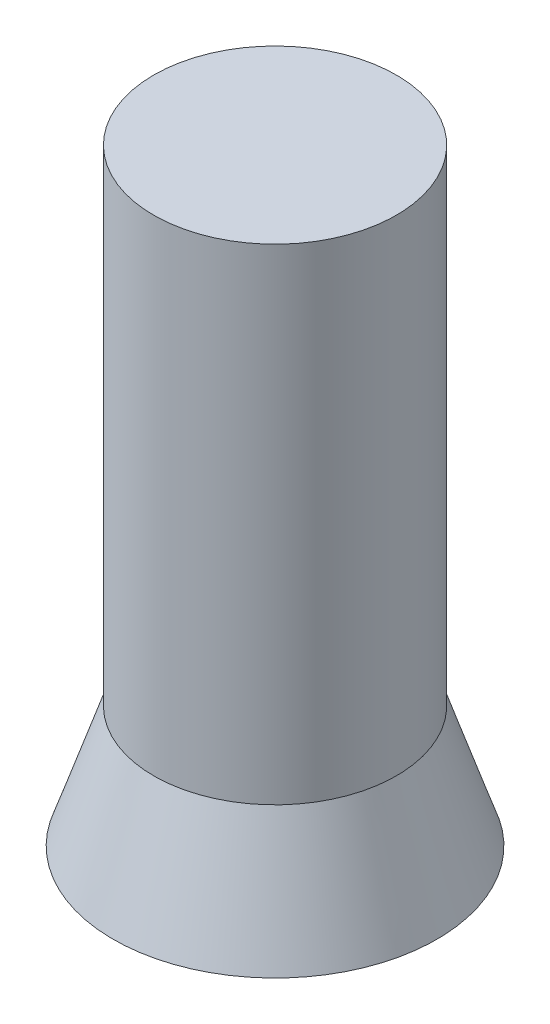
SolidWorks part; units mm, degrees
ref_plane "Front Plane" through (0, 0, 0) normal (0, 0, 1) x (1, 0, 0)
ref_plane "Top Plane" through (0, 0, 0) normal (0, 1, 0) x (1, 0, 0)
ref_plane "Right Plane" through (0, 0, 0) normal (1, 0, 0) x (0, 0, -1)
sketch "Sketch1" plane through (0, 0, 0) normal (0, 0, 1) x (1, 0, 0)
  line L0 (-3.175, 0) -> (3.175, 0)
  line L1 (-3.175, 0) -> (-2.3813, 2.3813)
  line L2 (-2.3813, 2.3813) -> (2.3813, 2.3813) construction
  line L3 (2.3813, 2.3813) -> (3.175, 0)
  line L4 (-2.3813, 2.3813) -> (-2.3813, 11.9062)
  line L5 (-2.3813, 11.9062) -> (2.3812, 11.9062)
  line L6 (2.3812, 11.9062) -> (2.3813, 2.3813)
  line L7 (0, 0) -> (0, -14.5981) construction
  line L8 (0, 0) -> (0, 11.9062)
  point P3 (0, 0)
  point P9 (0, 2.3813)
  dimension "D1" = 4.7625
  dimension "D2" = 6.35
  dimension "D3" = 2.3813
  dimension "D4" = 9.525
revolve "Revolve3" add sketch "Sketch1" angle 360 about L7
